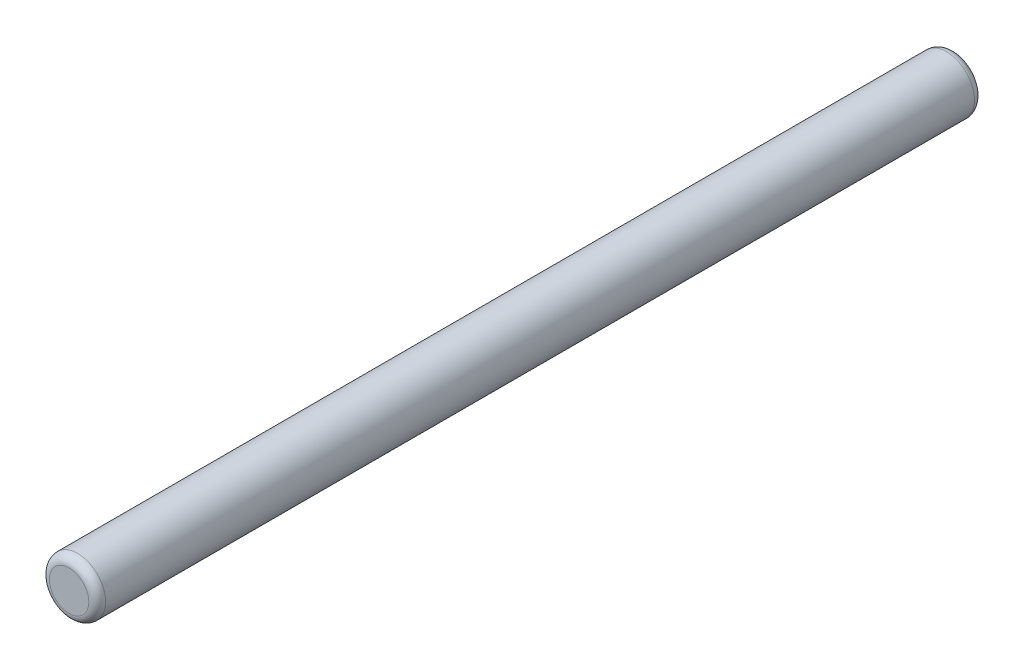
SolidWorks part; units mm, degrees
ref_plane "Front Plane" through (0, 0, 0) normal (0, 0, 1) x (1, 0, 0)
ref_plane "Top Plane" through (0, 0, 0) normal (0, 1, 0) x (1, 0, 0)
ref_plane "Right Plane" through (0, 0, 0) normal (1, 0, 0) x (0, 0, -1)
sketch "Sketch1" plane through (0, 0, 0) normal (0, 0, 1) x (1, 0, 0)
  circle A0 centre (0, 0) radius 0.5
  dimension "D1" = 1
extrude "Boss-Extrude1" add sketch "Sketch1" along normal blind 15.75
fillet "Fillet1" radius 0.15 2 edges at (0.5, 0, 0) (0.5, 0, 15.75)
